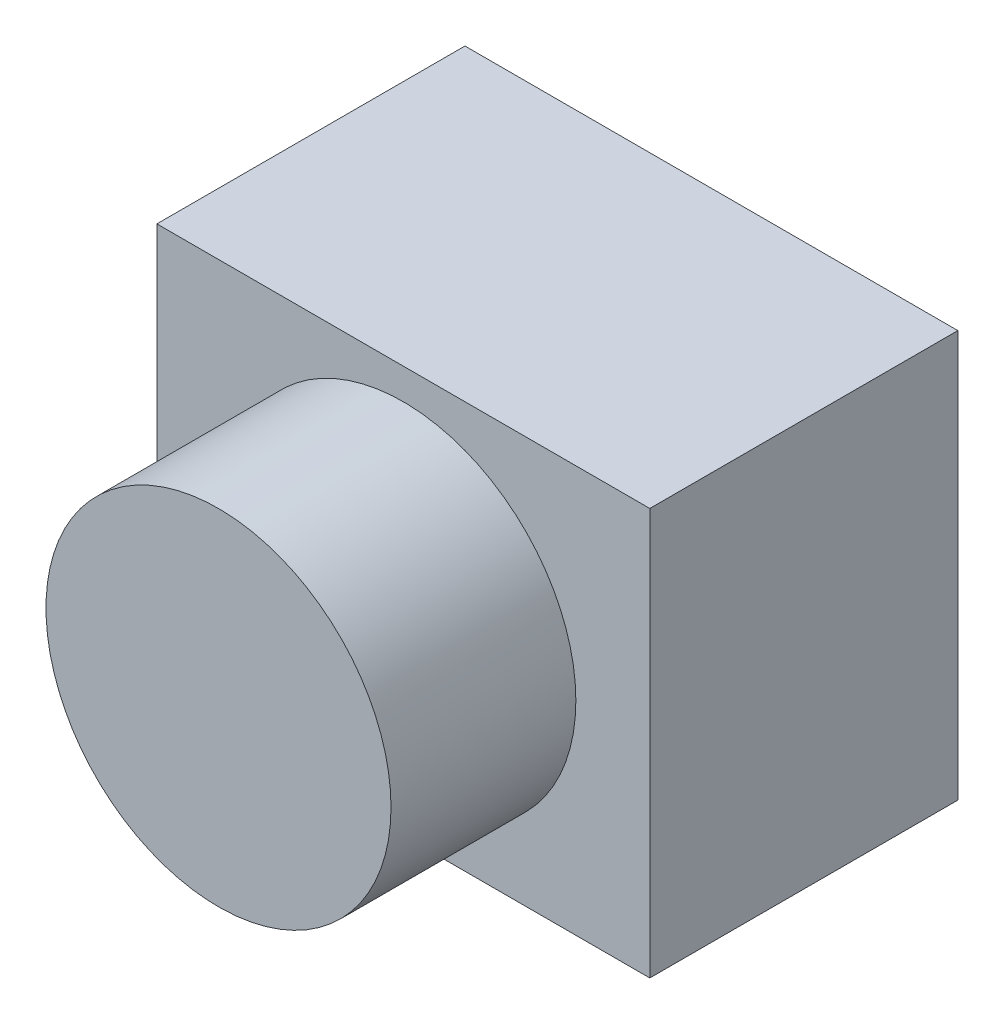
SolidWorks part; units mm, degrees
ref_plane "Front Plane" through (0, 0, 0) normal (0, 0, 1) x (1, 0, 0)
ref_plane "Top Plane" through (0, 0, 0) normal (0, 1, 0) x (1, 0, 0)
ref_plane "Right Plane" through (0, 0, 0) normal (1, 0, 0) x (0, 0, -1)
sketch "Sketch2" plane through (0, 0, 0) normal (0, 0, 1) x (1, 0, 0)
  line L1 (-33.0435, 32.9348) -> (46.9565, 32.9348)
  line L2 (-33.0435, 32.9348) -> (-33.0435, -33.0652)
  line L3 (-33.0435, -33.0652) -> (46.9565, -33.0652)
  line L4 (46.9565, 32.9348) -> (46.9565, -33.0652)
  dimension "D1" = 80
  dimension "D2" = 66
extrude "Boss-Extrude2" add sketch "Sketch2" along normal blind 50
sketch "Sketch4" plane through (0, 0, 50) normal (0, 0, 1) x (1, 0, 0)
  line L0 (46.9565, 32.9348) -> (-33.0435, 32.9348) construction
  line L3 (46.9565, -33.0652) -> (46.9565, 32.9348) construction
  circle A0 centre (6.9565, -0.0652) radius 28
  point P6 (46.9565, 1.2346)
  point P7 (46.9565, -1.3512)
  dimension "D1" = 56
  dimension "D2" = 33
  dimension "D3" = 40
extrude "Boss-Extrude3" add sketch "Sketch4" along normal blind 30
